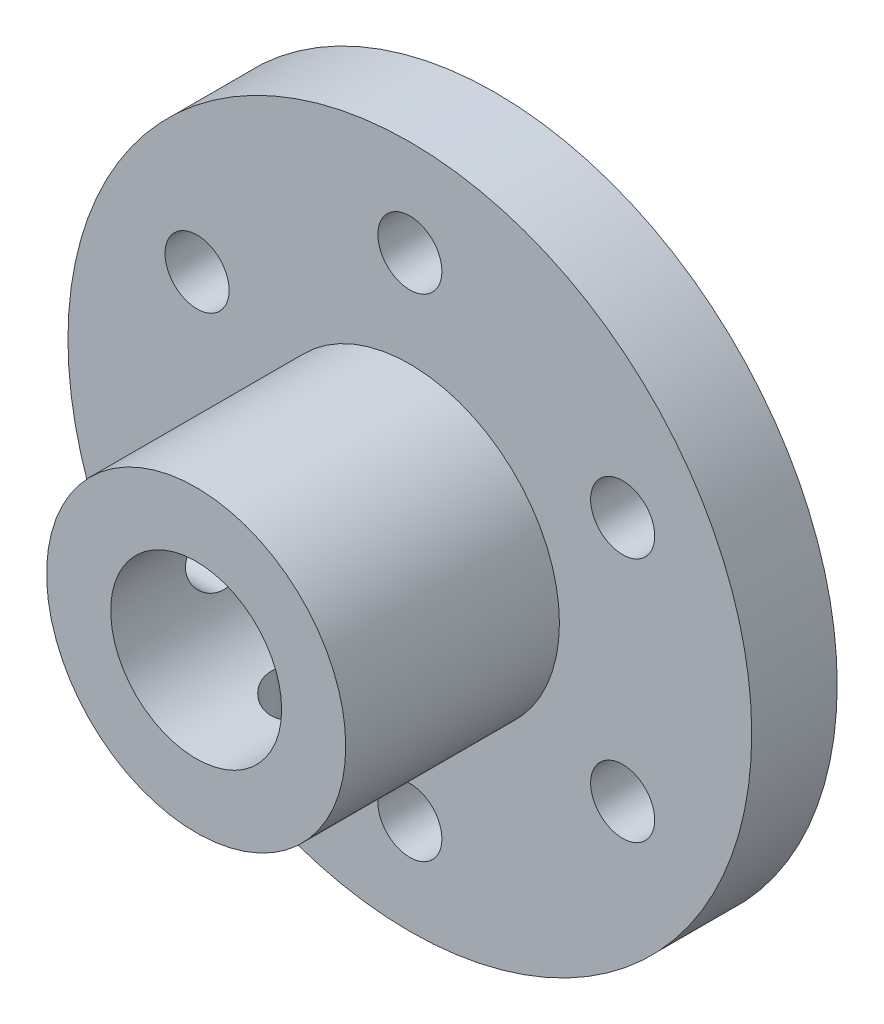
SolidWorks part; units mm, degrees
ref_plane "前视基准面" through (0, 0, 0) normal (0, 0, 1) x (1, 0, 0)
ref_plane "上视基准面" through (0, 0, 0) normal (0, 1, 0) x (1, 0, 0)
ref_plane "右视基准面" through (0, 0, 0) normal (1, 0, 0) x (0, 0, -1)
sketch "草图1" plane through (0, 0, 0) normal (0, 0, 1) x (1, 0, 0)
  circle A0 centre (0, 0) radius 16
  circle A1 centre (0, 0) radius 4
  circle A2 centre (0, 0) radius 11.5 construction
  circle A3 centre (0, -11.5) radius 1.5
  circle A4 centre (-9.9593, -5.75) radius 1.5
  circle A5 centre (-9.9593, 5.75) radius 1.5
  circle A6 centre (0, 11.5) radius 1.5
  circle A7 centre (9.9593, 5.75) radius 1.5
  circle A8 centre (9.9593, -5.75) radius 1.5
  dimension "D1" = 8
  dimension "D2" = 32
  dimension "D3" = 23
  dimension "D4" = 3
  dimension "D5" = 6
extrude "凸台-拉伸1" add sketch "草图1" along normal blind 4
sketch "草图2" plane through (0, 0, 4) normal (0, 0, 1) x (1, 0, 0)
  circle A0 centre (0, 0) radius 4
  circle A1 centre (0, 0) radius 7
  dimension "D1" = 14
  dimension "D2" = 3
extrude "凸台-拉伸2" add sketch "草图2" along normal blind 10
sketch "草图3" plane through (0, 0, 0) normal (0, 1, 0) x (1, 0, 0)
  line L0 (-7, -14) -> (7, -14) construction
  circle A0 centre (0, -9) radius 1.5
  dimension "D1" = 3
  dimension "D2" = 5
extrude "切除-拉伸1" cut sketch "草图3" against normal blind 10
sketch "草图4" plane through (0, 0, 0) normal (1, 0, 0) x (0, 0, -1)
  line L0 (-14, 7) -> (-14, -7) construction
  circle A0 centre (-9, 0) radius 1.5
  dimension "D1" = 5
extrude "切除-拉伸2" cut sketch "草图4" against normal blind 10
